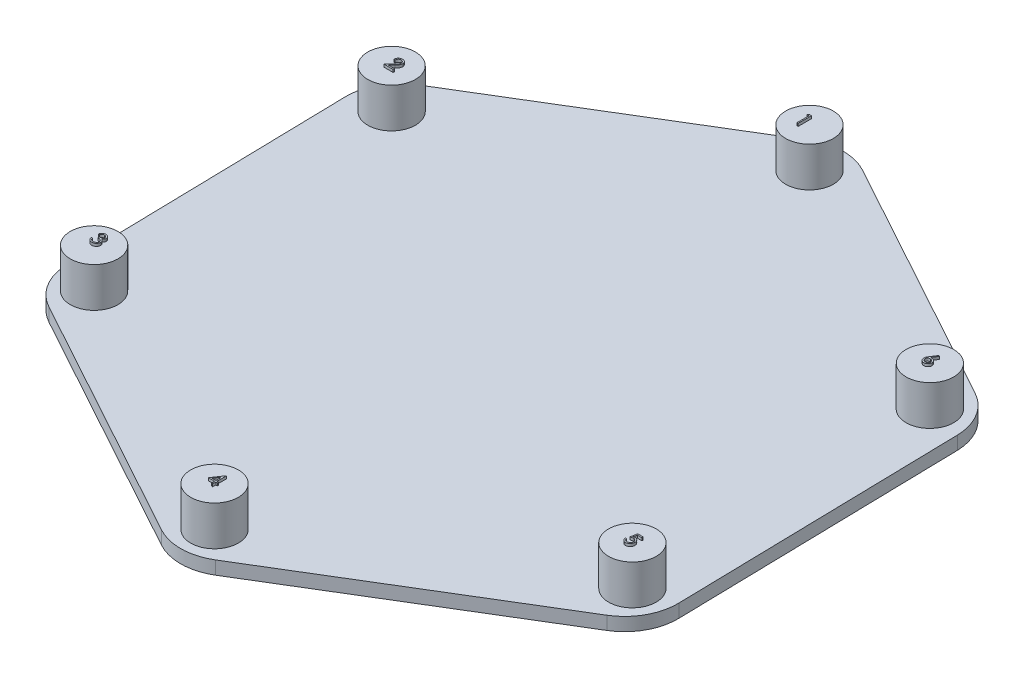
SolidWorks part; units mm, degrees
ref_plane "Front Plane" through (0, 0, 0) normal (0, 0, 1) x (1, 0, 0)
ref_plane "Top Plane" through (0, 0, 0) normal (0, 1, 0) x (1, 0, 0)
ref_plane "Right Plane" through (0, 0, 0) normal (1, 0, 0) x (0, 0, -1)
sketch "Sketch1" plane through (0, 0, 0) normal (0, 1, 0) x (1, 0, 0)
  line L0 (-28.5713, 1307.4229) -> (-1146.5471, 628.9679)
  line L1 (1068.6184, 648.5019) -> (-27.3099, 1249.7016)
  line L2 (-27.3099, 1249.7016) -> (-1095.9283, 601.1997)
  line L3 (-1095.9283, 601.1997) -> (-1068.6184, -648.5019)
  line L4 (-1068.6184, -648.5019) -> (27.3099, -1249.7016)
  line L5 (27.3099, -1249.7016) -> (1095.9283, -601.1997)
  line L6 (1095.9283, -601.1997) -> (1068.6184, 648.5019)
  line L7 (-1146.5471, 628.9679) -> (-1117.9758, -678.4549)
  line L8 (-1117.9758, -678.4549) -> (28.5713, -1307.4229)
  line L9 (28.5713, -1307.4229) -> (1146.5471, -628.9679)
  line L10 (1146.5471, -628.9679) -> (1117.9758, 678.4549)
  line L11 (1117.9758, 678.4549) -> (-28.5713, 1307.4229)
  circle A0 centre (0, 0) radius 1082.5318 construction
  dimension "D1" = 1250
  dimension "D2" = 2614.8458
  dimension "D3" = 50
extrude "Boss-Extrude1" add sketch "Sketch1" along normal mid plane 50
sketch "Sketch2" plane through (0, 25, 0) normal (0, 1, 0) x (1, 0, 0)
  line L6 (1117.9758, 678.4549) -> (-28.5713, 1307.4229)
  line L7 (-28.5713, 1307.4229) -> (-1146.5471, 628.9679)
  line L8 (-1146.5471, 628.9679) -> (-1117.9758, -678.4549)
  line L9 (-1117.9758, -678.4549) -> (28.5713, -1307.4229)
  line L10 (28.5713, -1307.4229) -> (1146.5471, -628.9679)
  line L11 (1146.5471, -628.9679) -> (1117.9758, 678.4549)
  line L12 (1117.9758, 678.4549) -> (-28.5713, 1307.4229)
  line L13 (-28.5713, 1307.4229) -> (-1146.5471, 628.9679)
  line L14 (-1146.5471, 628.9679) -> (-1117.9758, -678.4549)
  line L15 (-1117.9758, -678.4549) -> (28.5713, -1307.4229)
  line L16 (28.5713, -1307.4229) -> (1146.5471, -628.9679)
  line L17 (1146.5471, -628.9679) -> (1117.9758, 678.4549)
  dimension "D1" = 0
extrude "Boss-Extrude2" add sketch "Sketch2" against normal blind 10
sketch "Sketch3" plane through (0, 25, 0) normal (0, 1, 0) x (1, 0, 0)
  line L0 (-1146.5471, 628.9679) -> (0, 0) construction
  circle A0 centre (-1008.2541, 553.1037) radius 90
  circle A1 centre (0, 0) radius 150 construction
  dimension "D1" = 180
  dimension "D3" = 300
  dimension "D2" = 1150
extrude "Boss-Extrude3" add sketch "Sketch3" along normal blind 150
sketch "Sketch4" plane through (0, 0, 0) normal (1, 0, 0) x (0, 0, -1)
  line L0 (0, 0) -> (0, 25) construction
  line L1 (150, 25) -> (-150, 25) construction
pattern_circular "CirPattern1" count 6 over 360 about axis through (0, 0, 0) along (0, 1, 0) of "Boss-Extrude3"
sketch "Sketch5" plane through (0, 175, 0) normal (0, 1, 0) x (1, 0, 0)
  text T0 "1" font "Century Gothic" height 50
extrude "Boss-Extrude4" add sketch "Sketch5" along normal blind 10
sketch "Sketch6" plane through (0, 175, 0) normal (0, 1, 0) x (1, 0, 0)
  text T0 "2" font "Century Gothic" height 50
extrude "Boss-Extrude5" add sketch "Sketch6" along normal blind 10
sketch "Sketch7" plane through (0, 175, 0) normal (0, 1, 0) x (1, 0, 0)
  text T0 "3" font "Century Gothic" height 50
extrude "Boss-Extrude6" add sketch "Sketch7" along normal blind 10
sketch "Sketch8" plane through (0, 175, 0) normal (0, 1, 0) x (1, 0, 0)
  text T0 "4" font "Century Gothic" height 50
extrude "Boss-Extrude7" add sketch "Sketch8" along normal blind 10
sketch "Sketch9" plane through (0, 175, 0) normal (0, 1, 0) x (1, 0, 0)
  text T0 "5" font "Century Gothic" height 50
extrude "Boss-Extrude8" add sketch "Sketch9" along normal blind 10
sketch "Sketch10" plane through (0, 175, 0) normal (0, 1, 0) x (1, 0, 0)
  text T0 "6" font "Century Gothic" height 50
extrude "Boss-Extrude9" add sketch "Sketch10" along normal blind 10
fillet "Fillet1" radius 200 6 edges at (-1146.5471, 0, -628.9679) (-28.5713, 0, -1307.4229) (1146.5471, 0, 628.9679) (1117.9758, 0, -678.4549) (28.5713, 0, 1307.4229) (-1117.9758, 0, 678.4549)
sketch "Sketch12" plane through (0, 15, 0) normal (0, -1, 0) x (1, 0, 0)
  line L0 (-1068.6184, 648.5019) -> (-1019.1938, 618.5081) construction
  line L1 (-1087.018, 601.1812) -> (-1044.2371, 575.2192)
  line L2 (-1035.1379, 686.6707) -> (-992.357, 660.7087)
  line L3 (-1040.6358, 678.3098) -> (-997.8679, 652.3557)
  line L4 (-1091.8271, 592.4023) -> (-1049.0303, 566.4306)
  line L5 (-1042.6783, 691.2467) -> (1094.5585, -605.7572) construction
  line L6 (-1047.8663, 682.6977) -> (1089.3704, -614.3061) construction
  line L7 (-1094.5585, 605.7572) -> (1042.6783, -691.2467) construction
  line L8 (-1099.7465, 597.2082) -> (1037.4903, -699.7956) construction
  line L10 (-27.3099, -1249.7016) -> (-26.0468, -1191.9018) construction
  line L12 (-1095.9283, -601.1997) -> (-1045.2407, -573.3937) construction
  line L13 (-1112.2432, -553.1203) -> (-1068.369, -529.052)
  line L14 (-77.1053, -1239.791) -> (-76.012, -1189.7607)
  line L17 (-1064.1472, -640.7946) -> (-1020.273, -616.7263)
  line L18 (22.8708, -1241.9758) -> (23.9641, -1191.9455)
  line L21 (-1107.7514, -562.0621) -> (-1063.8906, -538.0011)
  line L22 (-1058.949, -649.3489) -> (-1015.0585, -625.2716)
  line L27 (32.8781, -1241.7512) -> (33.9718, -1191.7022)
  line L28 (-67.1156, -1240.3719) -> (-66.0226, -1190.3568)
  line L29 (-1119.9763, -557.3626) -> (-24.048, 43.8371) construction
  line L30 (-1115.1667, -566.13) -> (-19.2384, 35.0697) construction
  line L31 (-1071.8803, -645.0368) -> (24.048, -43.8371) construction
  line L32 (-1067.0707, -653.8043) -> (28.8576, -52.6046) construction
  line L33 (-77.298, -1248.6092) -> (-49.9881, 1.0924) construction
  line L34 (-67.3004, -1248.8277) -> (-39.9905, 0.8739) construction
  line L35 (22.6781, -1250.794) -> (49.9881, -1.0924) construction
  line L36 (32.6757, -1251.0125) -> (59.9857, -1.3109) construction
  line L37 (-1068.6184, 648.5019) -> (1068.6184, -648.5019) construction
  line L47 (-23.9641, 1191.9455) -> (-22.8708, 1241.9758)
  line L48 (-13.9583, 1192.1046) -> (-12.8653, 1242.1197)
  line L49 (26.0468, 1191.9018) -> (27.1392, 1241.8899) construction
  line L50 (76.012, 1189.7607) -> (77.1053, 1239.791)
  line L51 (85.9995, 1189.0805) -> (87.0932, 1239.1294)
  line L60 (-1095.9283, -601.1997) -> (0, 0) construction
  line L66 (-27.3099, -1249.7016) -> (0, 0) construction
  line L73 (986.7742, -669.018) -> (1029.5709, -694.9897)
  line L74 (992.357, -660.7087) -> (1035.1379, -686.6707)
  line L75 (1019.1938, -618.5081) -> (1061.9386, -644.4482) construction
  line L76 (1039.3721, -583.9641) -> (1082.1399, -609.9182)
  line L77 (1044.2371, -575.2192) -> (1087.018, -601.1812)
  line L78 (1072.7737, 520.0625) -> (1116.6642, 544.1398)
  line L79 (1068.369, 529.052) -> (1112.2432, 553.1203)
  line L80 (1045.2407, 573.3937) -> (1095.9283, 601.1997) construction
  line L82 (1025.4138, 608.1406) -> (1069.2746, 632.2015)
  line L83 (1020.273, 616.7263) -> (1064.1472, 640.7946)
  arc A0 (-1068.369, -529.052) -> (-1063.8906, -538.0011) centre (0, 0) ccw
  arc A1 (-1112.2432, -553.1203) -> (-1107.7514, -562.0621) centre (0, 0) ccw
  arc A2 (-1087.018, 601.1812) -> (-1091.8271, 592.4023) centre (0, 0) ccw
  circle A3 centre (0, 0) radius 1192.1864 construction
  circle A4 centre (0, 0) radius 1242.1864 construction
  arc A5 (-76.012, -1189.7607) -> (-66.0226, -1190.3568) centre (0, 0) ccw
  arc A6 (-77.1053, -1239.791) -> (-67.1156, -1240.3719) centre (0, 0) ccw
  arc A7 (1029.5709, -694.9897) -> (1035.1379, -686.6707) centre (0, 0) ccw
  arc A8 (986.7742, -669.018) -> (992.357, -660.7087) centre (0, 0) ccw
  arc A9 (1116.6642, 544.1398) -> (1112.2432, 553.1203) centre (0, 0) ccw
  arc A10 (1072.7737, 520.0625) -> (1068.369, 529.052) centre (0, 0) ccw
  arc A11 (87.0932, 1239.1294) -> (77.1053, 1239.791) centre (0, 0) ccw
  arc A12 (85.9995, 1189.0805) -> (76.012, 1189.7607) centre (0, 0) ccw
  arc A13 (-1035.1379, 686.6707) -> (-1040.6358, 678.3098) centre (0, 0) ccw
  arc A14 (-992.357, 660.7087) -> (-997.8679, 652.3557) centre (0, 0) ccw
  arc A15 (-1044.2371, 575.2192) -> (-1049.0303, 566.4306) centre (0, 0) ccw
  arc A16 (-13.9583, 1192.1046) -> (-23.9641, 1191.9455) centre (0, 0) ccw
  arc A17 (-12.8653, 1242.1197) -> (-22.8708, 1241.9758) centre (0, 0) ccw
  arc A18 (1069.2746, 632.2015) -> (1064.1472, 640.7946) centre (0, 0) ccw
  arc A19 (1025.4138, 608.1406) -> (1020.273, 616.7263) centre (0, 0) ccw
  arc A20 (1039.3721, -583.9641) -> (1044.2371, -575.2192) centre (0, 0) ccw
  arc A21 (1082.1399, -609.9182) -> (1087.018, -601.1812) centre (0, 0) ccw
  arc A22 (23.9641, -1191.9455) -> (33.9718, -1191.7022) centre (0, 0) ccw
  arc A23 (22.8708, -1241.9758) -> (32.8781, -1241.7512) centre (0, 0) ccw
  arc A24 (-1020.273, -616.7263) -> (-1015.0585, -625.2716) centre (0, 0) ccw
  arc A25 (-1064.1472, -640.7946) -> (-1058.949, -649.3489) centre (0, 0) ccw
  dimension "D5" = 2384.3727
  dimension "D9" = 42.7678
  dimension "D1" = 50
  dimension "D2" = 50
  dimension "D3" = 10
  dimension "D4" = 50
  dimension "D6" = 50
  dimension "D7" = 50
  dimension "D8" = 10
extrude "Boss-Extrude10" [suppressed] add sketch "Sketch12" along normal blind 20
sketch "Sketch13" plane through (0, 15, 0) normal (0, -1, 0) x (1, 0, 0)
  line L0 (26.2184, 1199.7536) -> (27.3099, 1249.7016) construction
  line L1 (36.2151, 1199.4934) -> (37.3076, 1249.4832)
  line L2 (16.2199, 1199.9304) -> (17.3123, 1249.9201)
  line L3 (17.3123, 1249.9201) -> (37.3076, 1249.4832)
  line L4 (-9.9976, 0.2185) -> (17.3123, 1249.9201) construction
  line L5 (0, 0) -> (27.3099, 1249.7016) construction
  line L6 (9.9976, -0.2185) -> (37.3076, 1249.4832) construction
  arc A0 (37.3076, 1249.4832) -> (17.3123, 1249.9201) centre (0, 0) ccw
  arc A1 (36.2151, 1199.4934) -> (16.2199, 1199.9304) centre (0, 0) ccw
  circle A2 centre (0, 0) radius 1250.04 construction
  circle A3 centre (0, 0) radius 1200.04 construction
  line M5 (1095.9283, 601.1997) -> (27.3099, 1249.7016)
  line M6 (27.3099, 1249.7016) -> (-1068.6184, 648.5019)
  dimension "D2" = 1250
  dimension "D4" = 1200.04
  dimension "D1" = 19.9952
  dimension "D3" = 50
extrude "Boss-Extrude11" add sketch "Sketch13" along normal blind 20 contours A1 L1 L2 M5 M6
sketch "Sketch14" plane through (0, 15, 0) normal (0, -1, 0) x (-1, 0, 0)
  circle A0 centre (0, 0) radius 25 construction
  dimension "D1" = 50
pattern_circular "CirPattern2" count 6 over 360 about axis through (0, 0, 0) along (0, 1, 0) of "Boss-Extrude11"
